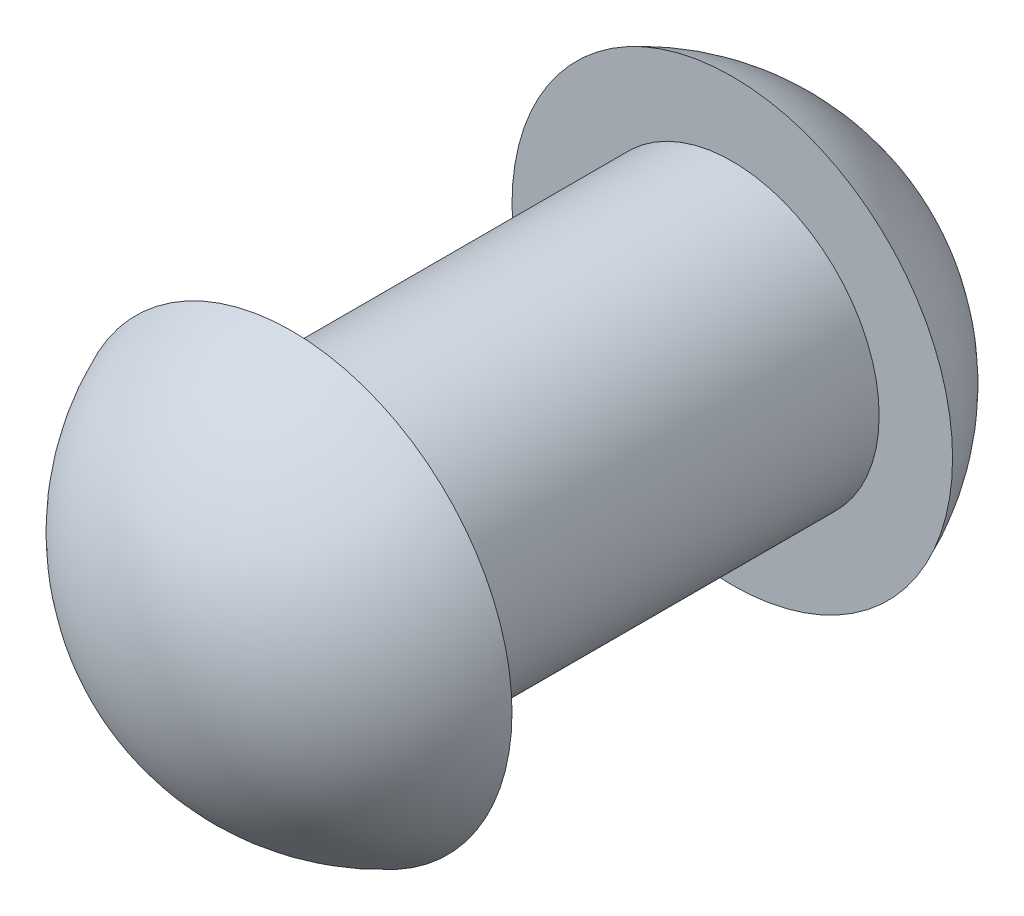
SolidWorks part; units mm, degrees
ref_plane "前视基准面" through (0, 0, 0) normal (0, 0, 1) x (1, 0, 0)
ref_plane "上视基准面" through (0, 0, 0) normal (0, 1, 0) x (1, 0, 0)
ref_plane "右视基准面" through (0, 0, 0) normal (1, 0, 0) x (0, 0, -1)
sketch "草图1" plane through (0, 0, 0) normal (0, 1, 0) x (1, 0, 0)
  line L0 (0, 2.5) -> (0, -2.5)
  line L1 (1.5, 1.5) -> (1, 1.5)
  line L2 (1, 1.5) -> (1, -1.5)
  line L3 (1, -1.5) -> (1.5, -1.5)
  arc A0 (0, 2.5) -> (1.5, 1.5) centre (0, 0.875) cw
  arc A1 (1.5, -1.5) -> (0, -2.5) centre (0, -0.875) cw
  point P3 (0, 0)
  point P10 (1, 0)
  dimension "D1" = 0.5
  dimension "D2" = 1
  dimension "D3" = 3
  dimension "D4" = 5
revolve "旋转1" add sketch "草图1" angle 360 about L0
scale "缩放比例1" scale about centroid uniform scaling yes scale factor 0.169231
